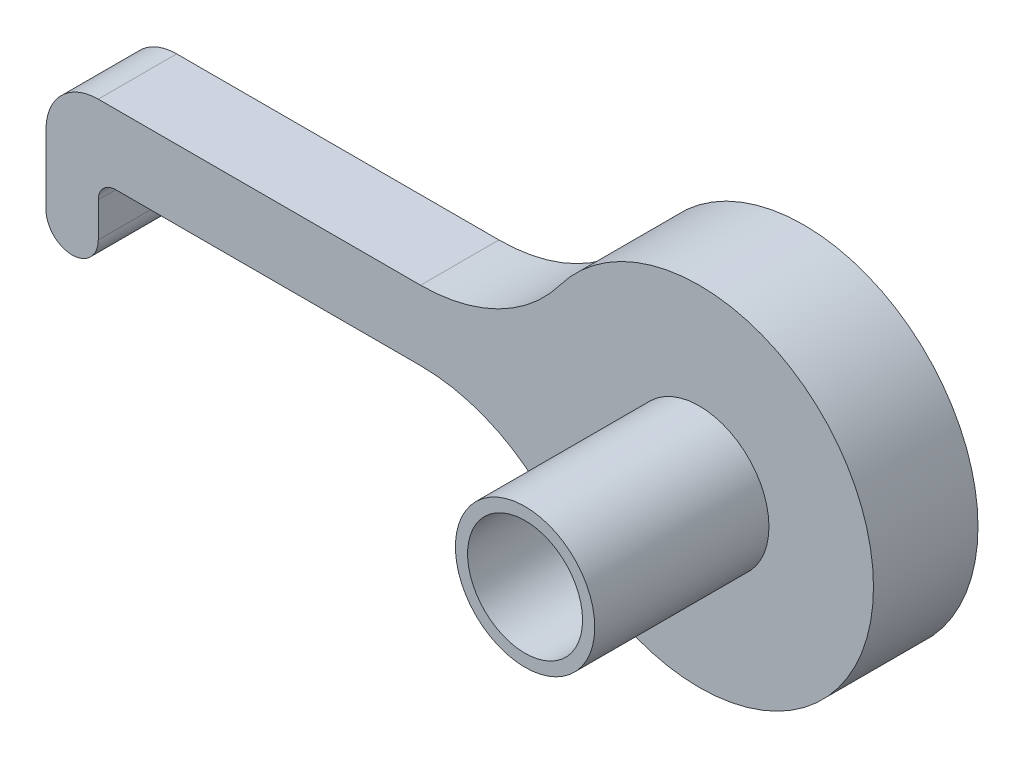
SolidWorks part; units mm, degrees
ref_plane "Plano frontal" through (0, 0, 0) normal (0, 0, 1) x (1, 0, 0)
ref_plane "Plano superior" through (0, 0, 0) normal (0, 1, 0) x (1, 0, 0)
ref_plane "Plano direito" through (0, 0, 0) normal (1, 0, 0) x (0, 0, -1)
sketch "Esboço1" plane through (0, 0, 0) normal (0, 0, 1) x (1, 0, 0)
  circle A0 centre (0, 0) radius 10
  dimension "D2" = 20
extrude "Ressalto-extrusão1" add sketch "Esboço1" along normal blind 6
sketch "Esboço2" plane through (0, 0, 6) normal (0, 0, 1) x (1, 0, 0)
  line L0 (-9.798, 2) -> (-37.5, 2)
  line L1 (-9.798, -2) -> (-34.5, -2)
  line L2 (-37.5, -5) -> (-37.5, 2)
  line L5 (-34.5, -5) -> (-34.5, -2)
  arc A0 (-9.798, 2) -> (-9.798, -2) centre (0, 0) ccw
  arc A1 (-37.5, -5) -> (-34.5, -5) centre (-36, -5) ccw
  circle A3 centre (0, 0) radius 10 construction
  point P11 (0, 0)
  dimension "D2" = 5
  dimension "D5" = 36
  dimension "D6" = 10
  dimension "D1" = 3
  dimension "D3" = 2
  dimension "D4" = 2
  dimension "D7" = 0
extrude "Ressalto-extrusão2" add sketch "Esboço2" against normal blind 4.5
fillet "Filete1" radius 3 1 edges at (-37.5, 2, 3.75)
fillet "Filete2" radius 1 1 edges at (-34.5, -2, 3.75)
fillet "Filete3" radius 10 2 edges at (-9.798, -2, 3.75) (-9.798, 2, 3.75)
sketch "Esboço3" plane through (0, 0, 6) normal (0, 0, 1) x (1, 0, 0)
  circle A0 centre (0, 0) radius 4
  dimension "D1" = 8
extrude "Ressalto-extrusão3" add sketch "Esboço3" along normal blind 10
sketch "Esboço4" plane through (0, 0, 16) normal (0, 0, 1) x (1, 0, 0)
  circle A0 centre (0, 0) radius 3.3
  dimension "D1" = 6.6
extrude "Corte-extrusão1" cut sketch "Esboço4" against normal offset from surface (14 mm away) 2 up to face at (10, 0, 0)
